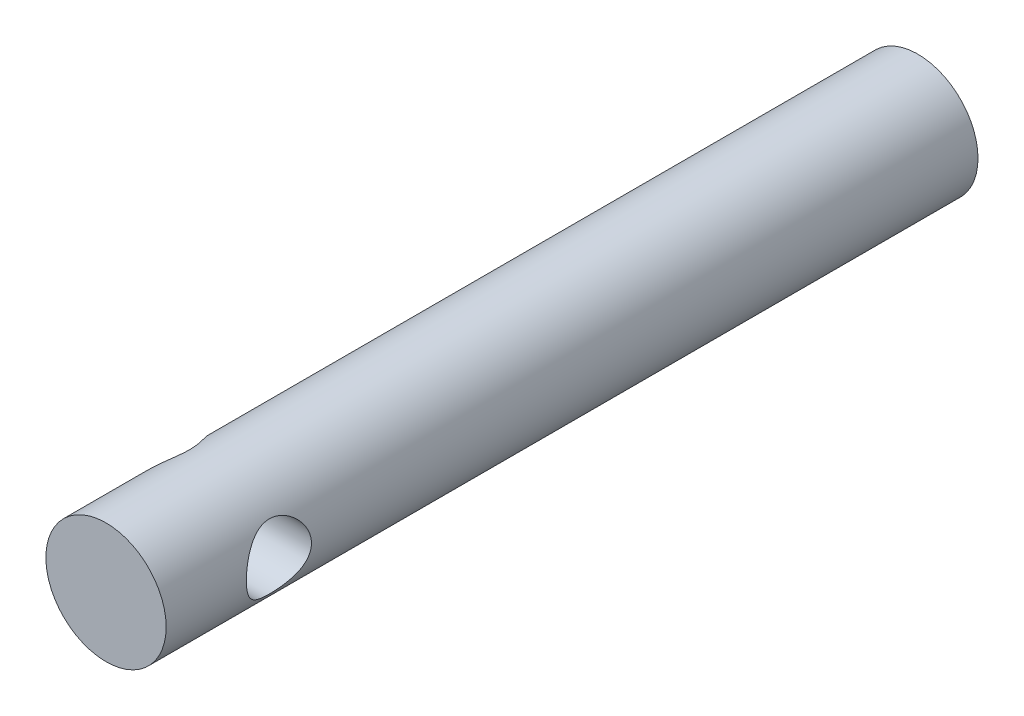
SolidWorks part; units mm, degrees
ref_plane "Front Plane" through (0, 0, 0) normal (0, 0, 1) x (1, 0, 0)
ref_plane "Top Plane" through (0, 0, 0) normal (0, 1, 0) x (1, 0, 0)
ref_plane "Right Plane" through (0, 0, 0) normal (1, 0, 0) x (0, 0, -1)
sketch "Sketch1" plane through (0, 0, 0) normal (0, 0, 1) x (1, 0, 0)
  circle A0 centre (0, 0) radius 4
extrude "Boss-Extrude1" add sketch "Sketch1" along normal blind 54.0026
sketch "Sketch2" plane through (0, 0, 0) normal (1, 0, 0) x (0, 0, -1)
  line L0 (-54.0026, -4) -> (0, -4) construction
  line L1 (-54.0026, 4) -> (-39.0026, 4) construction
  line L2 (-54.0026, 4) -> (-54.0026, -4) construction
  line L3 (-54.0026, -4) -> (-39.0026, -4) construction
  line L4 (-39.0026, 4) -> (-39.0026, -4) construction
  line L5 (-54.0026, 4) -> (-39.0026, -4) construction
  line L6 (-39.0026, 4) -> (-54.0026, -4) construction
  circle A0 centre (-46.5026, 0) radius 2.165
  dimension "D2" = 4.33
  dimension "D1" = 15
extrude "Cut-Extrude1" cut sketch "Sketch2" against normal mid plane 18
sketch "Sketch4" plane through (0, 0, 0) normal (1, 0, 0) x (0, 0, -1)
  circle A0 centre (-46.5026, 0) radius 3.5
extrude "Cut-Extrude2" cut sketch "Sketch4" against normal through all
